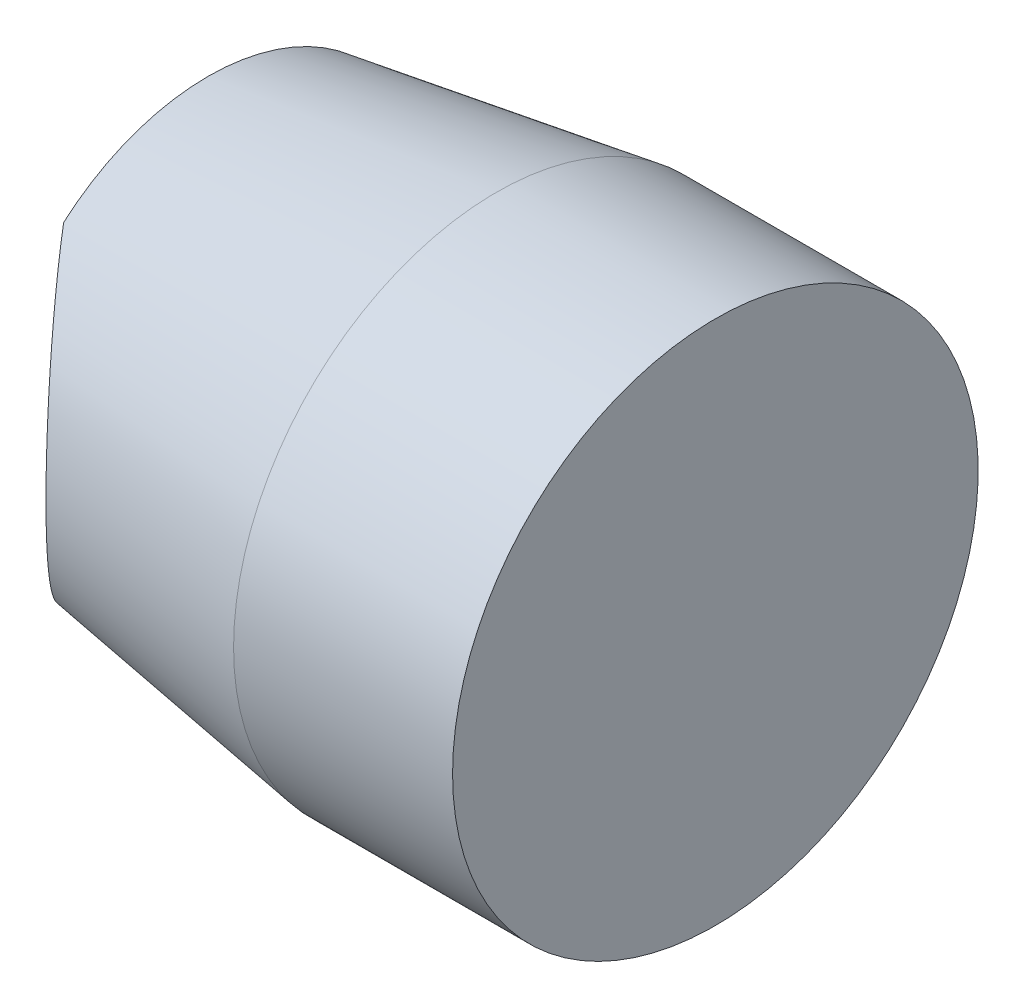
SolidWorks part; units mm, degrees
ref_plane "Alzado" through (0, 0, 0) normal (0, 0, 1) x (1, 0, 0)
ref_plane "Planta" through (0, 0, 0) normal (0, 1, 0) x (1, 0, 0)
ref_plane "Vista lateral" through (0, 0, 0) normal (1, 0, 0) x (0, 0, -1)
sketch "Croquis1" plane through (0, 0, 0) normal (0, 0, 1) x (1, 0, 0)
  line L0 (0, 0) -> (6.95, 0)
  line L1 (6.95, 0) -> (6.95, 3.6)
  line L2 (6.95, 3.6) -> (3.95, 3.6)
  line L3 (3.95, 3.6) -> (0, 3)
  line L4 (0, 3) -> (0, 0)
  dimension "D1" = 3.6
  dimension "D2" = 3
  dimension "D3" = 3.95
  dimension "D4" = 3
revolve "Revolución1" add sketch "Croquis1" angle 360 about L0
sketch "Croquis2" plane through (0, 0, 0) normal (0, 0, 1) x (1, 0, 0)
  line L0 (-37, 2.5691) -> (-37, -2.4825) construction
  circle A0 centre (-2, 0) radius 3.05
  dimension "D2" = 6.1
  dimension "D1" = 37
  dimension "D3" = 2
revolve "Cortar-Revolución1" cut sketch "Croquis2" angle 360 about L0
